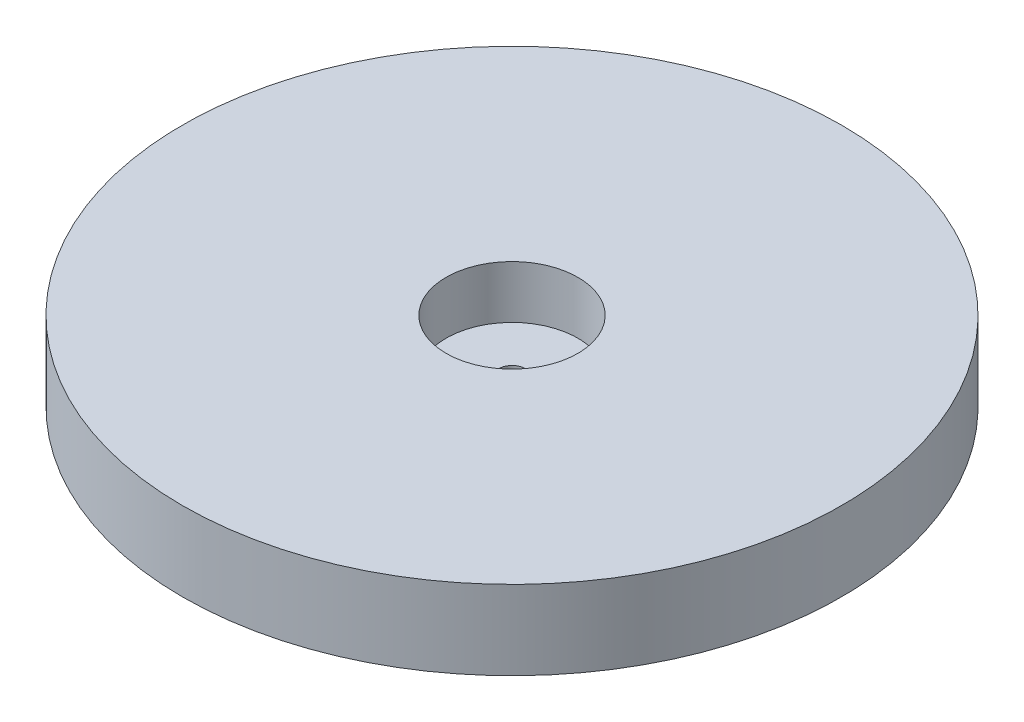
SolidWorks part; units mm, degrees
ref_plane "Plan de face" through (0, 0, 0) normal (0, 0, 1) x (1, 0, 0)
ref_plane "Plan de dessus" through (0, 0, 0) normal (0, 1, 0) x (1, 0, 0)
ref_plane "Plan de droite" through (0, 0, 0) normal (1, 0, 0) x (0, 0, -1)
sketch "Esquisse1" plane through (0, 0, 0) normal (0, 1, 0) x (1, 0, 0)
  circle A0 centre (0, 0) radius 50
extrude "Boss.-Extru.1" add sketch "Esquisse1" along normal blind 12
sketch "Esquisse2" plane through (0, 12, 0) normal (0, 1, 0) x (1, 0, 0)
  circle A0 centre (0, 0) radius 10
extrude "Enlèv. mat.-Extru.1" cut sketch "Esquisse2" against normal blind 8
sketch "Esquisse4" plane through (0, 12, 0) normal (0, 1, 0) x (1, 0, 0)
  circle A0 centre (0, 0) radius 2
extrude "Enlèv. mat.-Extru.4" cut sketch "Esquisse4" against normal blind 12
